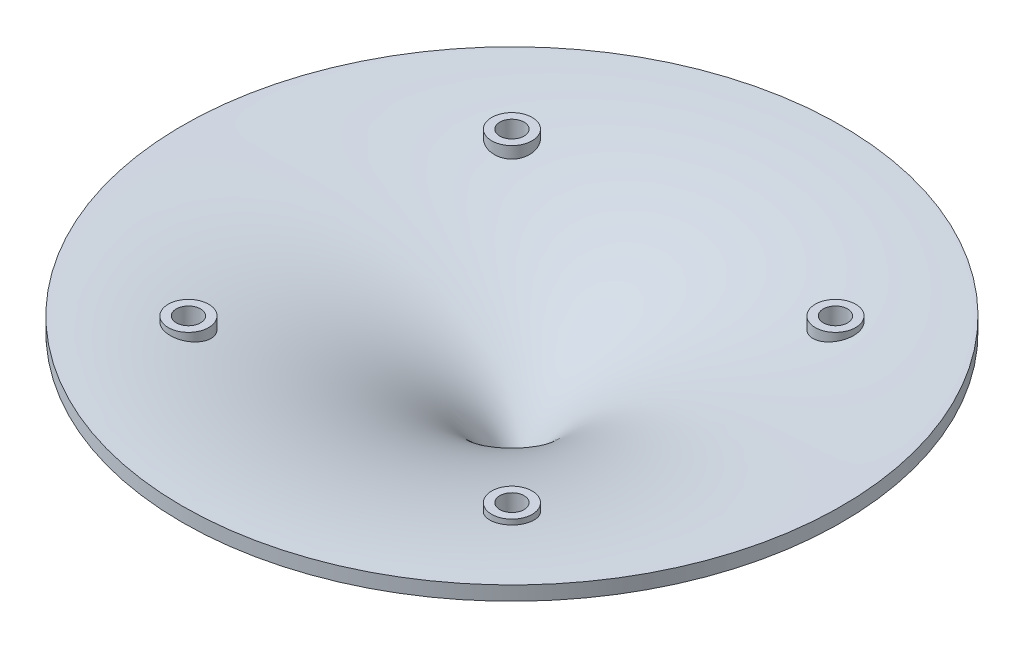
SolidWorks part; units mm, degrees
ref_plane "Front Plane" through (0, 0, 0) normal (0, 0, 1) x (1, 0, 0)
ref_plane "Top Plane" through (0, 0, 0) normal (0, 1, 0) x (1, 0, 0)
ref_plane "Right Plane" through (0, 0, 0) normal (1, 0, 0) x (0, 0, -1)
sketch "Sketch1" plane through (0, 0, 0) normal (0, 0, 1) x (1, 0, 0)
  line L0 (55, 0) -> (-55, 0) construction
  line L1 (1.5, 0) -> (81.5, 0) construction
  line L2 (1.5, 0) -> (1.5, 40) construction
  line L3 (1.5, 40) -> (81.5, 40) construction
  line L4 (81.5, 0) -> (81.5, 40) construction
  line L5 (0, -55) -> (0, 55) construction
  line L6 (85.3, 43.4357) -> (85.3, -3.4112) construction
  line L7 (3.8, 0) -> (3.8, 31.6103) construction
  line L8 (97.6356, 36.5) -> (-14.2512, 36.5) construction
  line L9 (3.8, 7.1341) -> (3.8, -12.5375) construction
  line L10 (94.0146, 36.5) -> (68.9798, 36.5) construction
  line L11 (3.8, 0) -> (3.8, -15)
  line L12 (3.8, -15) -> (1.5, -15)
  line L13 (1.5, -15) -> (1.5, 0)
  line L14 (81.5, 40) -> (81.5, 36.5)
  line L15 (0, 59.5062) -> (0, -62.5384) construction
  ellipse E0 centre (81.5, 0) end of major axis (1.5, 0) minor radius 40 (81.5, 40) -> (1.5, 0) ccw
  spline S0 degree 3 poles (3.8, 0) (3.8, 6.3357) (17.7181, 21.3859) (45.3457, 33.2487) (66.206, 36.5) (81.5, 36.5) knots 0 0 0 0 0.319283 0.419283 1 1 1 1
  dimension "D1" = 1.5
  dimension "D2" = 40
  dimension "D3" = 80
  dimension "D4" = 3.8
  dimension "D5" = 3.8
  dimension "D6" = 3.5
  dimension "D7" = 15
revolve "Revolve1" add sketch "Sketch1" angle 360 about L15
sketch "Sketch2" plane through (0, 0, 0) normal (0, 1, 0) x (1, 0, 0)
  line L0 (-30.25, 0) -> (30.25, 0) construction
  line L1 (0, -30.25) -> (0, 30.25) construction
  line L2 (0, 105.9171) -> (0, -111.2885) construction
  line L3 (122.8813, 0) -> (-105.0671, 0) construction
  circle A0 centre (-40, 40) radius 3
  circle A1 centre (40, 40) radius 3
  circle A2 centre (40, -40) radius 3
  circle A3 centre (-40, -40) radius 3
  dimension "D1" = 6
  dimension "D2" = 40
  dimension "D3" = 40
extrude "Cut-Extrude3" cut sketch "Sketch2" along normal blind 100
ref_plane "Plane1" through (0, 40, 0) normal (0, 1, 0) x (1, 0, 0)
sketch "Sketch3" plane through (0, 40, 0) normal (0, 1, 0) x (1, 0, 0)
  line L0 (0, 94.0693) -> (0, -94.3024) construction
  line L1 (0, -30.25) -> (0, 30.25) construction
  line L2 (100.7136, 0) -> (-96.0509, 0) construction
  line L3 (-30.25, 0) -> (30.25, 0) construction
  circle A0 centre (40, 40) radius 5
  circle A1 centre (40, 40) radius 3
  circle A2 centre (-40, 40) radius 5
  circle A3 centre (-40, 40) radius 3
  circle A4 centre (-40, -40) radius 5
  circle A5 centre (-40, -40) radius 3
  circle A6 centre (40, -40) radius 5
  circle A7 centre (40, -40) radius 3
  dimension "D1" = 10
  dimension "D2" = 6
extrude "Boss-Extrude1" add sketch "Sketch3" against normal up to surface (2.5957 mm away)
